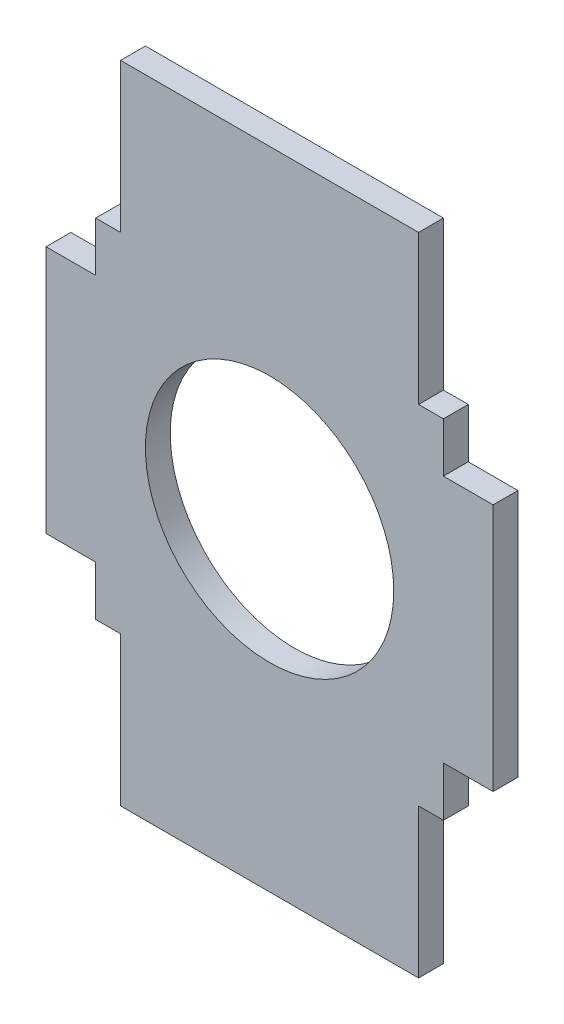
SolidWorks part; units mm, degrees
ref_plane "Front Plane" through (0, 0, 0) normal (0, 0, 1) x (1, 0, 0)
ref_plane "Top Plane" through (0, 0, 0) normal (0, 1, 0) x (1, 0, 0)
ref_plane "Right Plane" through (0, 0, 0) normal (1, 0, 0) x (0, 0, -1)
sketch "Sketch1" plane through (0, 0, 0) normal (0, 0, 1) x (1, 0, 0)
  line L1 (-0.5585, 289.0723) -> (37.5415, 289.0723)
  line L2 (-10.0835, 346.2223) -> (-10.0835, 314.4723)
  line L4 (47.0665, 346.2223) -> (47.0665, 314.4723)
  line L6 (-3.7335, 258.914) -> (-3.7335, 314.4723) construction
  line L9 (-10.0835, 346.2223) -> (-3.7335, 346.2223)
  line L10 (-3.7335, 352.5723) -> (-3.7335, 346.2223)
  line L11 (40.7165, 258.914) -> (40.7165, 308.1223) construction
  line L14 (-10.0835, 314.4723) -> (-3.7335, 314.4723)
  line L15 (-3.7335, 308.1223) -> (-3.7335, 314.4723)
  line L18 (47.0665, 314.4723) -> (40.7165, 314.4723)
  line L19 (40.7165, 308.1223) -> (40.7165, 314.4723)
  line L20 (40.7165, 258.914) -> (40.7165, 314.4723) construction
  line L23 (47.0665, 346.2223) -> (40.7165, 346.2223)
  line L24 (40.7165, 352.5723) -> (40.7165, 346.2223)
  line L26 (-0.5585, 371.6223) -> (-0.5585, 352.5723)
  line L27 (-0.5585, 352.5723) -> (-3.7335, 352.5723)
  line L30 (-0.5585, 289.0723) -> (-0.5585, 308.1223)
  line L31 (-0.5585, 308.1223) -> (-3.7335, 308.1223)
  line L34 (37.5415, 289.0723) -> (37.5415, 308.1223)
  line L35 (37.5415, 308.1223) -> (40.7165, 308.1223)
  line L37 (-0.5585, 371.6223) -> (37.5415, 371.6223)
  line L39 (37.5415, 371.6223) -> (37.5415, 352.5723)
  line L40 (37.5415, 352.5723) -> (40.7165, 352.5723)
  circle A0 centre (18.4915, 330.3473) radius 15.875
  dimension "D1" = 31.75
  dimension "D2" = 6.35
  dimension "D3" = 6.35
  dimension "D6" = 6.35
  dimension "D7" = 6.35
extrude "Boss-Extrude1" add sketch "Sketch1" against normal blind 3.175 contours L37 L39 L40 L24 L23 L4 L18 L19 L35 L34 L1 L30 L31 L15 L14 L2 L9 L10 L27 L26
